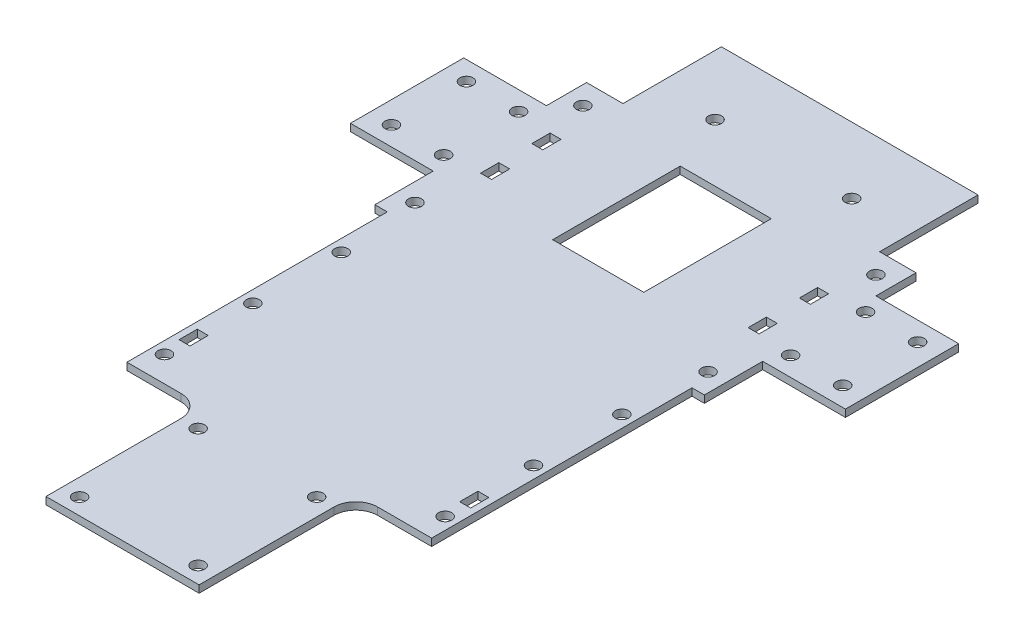
SolidWorks part; units mm, degrees
ref_plane "前视基准面" through (0, 0, 0) normal (0, 0, 1) x (1, 0, 0)
ref_plane "上视基准面" through (0, 0, 0) normal (0, 1, 0) x (1, 0, 0)
ref_plane "右视基准面" through (0, 0, 0) normal (1, 0, 0) x (0, 0, -1)
sketch "Sketch1" plane through (0, 0, 0) normal (0, 1, 0) x (1, 0, 0)
  line L1 (0, 0) -> (50, 0)
  line L2 (0, 0) -> (0, 9.1)
  line L3 (0, 9.1) -> (50, 9.1)
  line L4 (50, 0) -> (50, 9.1)
  dimension "D1" = 50
  dimension "D2" = 9.1
extrude "Boss-Extrude1" add sketch "Sketch1" along normal blind 2
sketch "Sketch2" plane through (0, 2, 0) normal (0, 1, 0) x (1, 0, 0)
  line L0 (50, 9.1) -> (0, 9.1) construction
  line L1 (12.5, 9.1) -> (37.5, 9.1)
  line L2 (12.5, 9.1) -> (12.5, 2.5)
  line L3 (12.5, 2.5) -> (37.5, 2.5)
  line L4 (37.5, 9.1) -> (37.5, 2.5)
  line L5 (0, 9.1) -> (0, 0) construction
  line L6 (50, 0) -> (50, 9.1) construction
  point P8 (50, 4.55)
  dimension "D1" = 6.6
  dimension "D2" = 12.5
  dimension "D3" = 12.5
extrude "Cut-Extrude1" cut sketch "Sketch2" against normal blind 2
sketch "Sketch3" plane through (0, 2, 0) normal (0, 1, 0) x (1, 0, 0)
  line L0 (12.5, 9.1) -> (0, 9.1) construction
  line L1 (50, 9.1) -> (37.5, 9.1) construction
  line L3 (37.5, 2.5) -> (37.5, 9.1) construction
  line L5 (0, 9.1) -> (0, 0) construction
  circle A0 centre (6.25, 5.8) radius 1.8
  circle A1 centre (43.75, 5.8) radius 1.8
  dimension "D1" = 3.6
  dimension "D2" = 3.6
  dimension "D4" = 3.3
  dimension "D3" = 3.3
  dimension "D5" = 6.25
  dimension "D6" = 6.25
extrude "Cut-Extrude2" cut sketch "Sketch3" against normal blind 2
sketch "Sketch4" plane through (0, 2, 0) normal (0, 1, 0) x (1, 0, 0)
  line L0 (0, 0) -> (50, 0) construction
  line L1 (-8.2, 0) -> (58.2, 0)
  line L2 (-8.2, 0) -> (-8.2, -130)
  line L3 (-8.2, -130) -> (58.2, -130)
  line L4 (58.2, 0) -> (58.2, -130)
  line L5 (12.5, 2.5) -> (37.5, 2.5) construction
  point P6 (25, 2.5)
  dimension "D1" = 130
  dimension "D2" = 0
  dimension "D3" = 33.2
  dimension "D4" = 66.4
extrude "Boss-Extrude2" add sketch "Sketch4" against normal blind 2
sketch "Sketch5" plane through (0, 0, 130) normal (0, 0, 1) x (1, 0, 0)
  line L1 (-8.2, 2) -> (58.2, 2)
  line L2 (-8.2, 2) -> (-8.2, 0)
  line L3 (-8.2, 0) -> (58.2, 0)
  line L4 (58.2, 2) -> (58.2, 0)
extrude "Boss-Extrude3" add sketch "Sketch5" along normal blind 2.5
sketch "Sketch6" plane through (0, 2, 0) normal (0, 1, 0) x (1, 0, 0)
  line L1 (-8.2, -132.5) -> (-16.8, -132.5)
  line L2 (-8.2, -132.5) -> (-8.2, -70)
  line L3 (-8.2, -70) -> (-16.8, -70)
  line L4 (-16.8, -132.5) -> (-16.8, -70)
  line L5 (58.2, -132.5) -> (66.8, -132.5)
  line L6 (58.2, -132.5) -> (58.2, -70)
  line L7 (58.2, -70) -> (66.8, -70)
  line L8 (66.8, -132.5) -> (66.8, -70)
  dimension "D1" = 8.6
  dimension "D2" = 8.6
  dimension "D3" = 62.5
  dimension "D4" = 62.5
extrude "Boss-Extrude4" add sketch "Sketch6" against normal blind 2
sketch "Sketch7" plane through (0, 2, 0) normal (0, 1, 0) x (1, 0, 0)
  line L0 (-13.5, -64.2883) -> (-13.5, -157.5169) construction
  line L1 (63.5, -64.2883) -> (63.5, -152.5529) construction
  line L2 (-16.8, -70) -> (-16.8, -132.5) construction
  line L3 (66.8, -132.5) -> (66.8, -70) construction
  line L4 (-8.2, -70) -> (-16.8, -70) construction
  line L5 (66.8, -132.5) -> (-16.8, -132.5) construction
  line L6 (66.8, -70) -> (58.2, -70) construction
  line L7 (-15, -115) -> (-12, -115)
  line L8 (-15, -115) -> (-15, -120)
  line L9 (-15, -120) -> (-12, -120)
  line L10 (-12, -115) -> (-12, -120)
  line L11 (62, -115) -> (65, -115)
  line L12 (62, -115) -> (62, -120)
  line L13 (62, -120) -> (65, -120)
  line L14 (65, -115) -> (65, -120)
  circle A0 centre (-13.5, -77) radius 1.8
  circle A1 centre (-13.5, -101.25) radius 1.8
  circle A2 centre (-13.5, -125.5) radius 1.8
  circle A3 centre (63.5, -77) radius 1.8
  circle A4 centre (63.5, -101.25) radius 1.8
  circle A5 centre (63.5, -125.5) radius 1.8
  dimension "D3" = 3.6
  dimension "D4" = 3.6
  dimension "D6" = 3.6
  dimension "D12" = 3.6
  dimension "D13" = 3.6
  dimension "D14" = 3.6
  dimension "D1" = 3.3
  dimension "D2" = 3.3
  dimension "D5" = 31.25
  dimension "D7" = 7
  dimension "D8" = 1.5
  dimension "D9" = 3
  dimension "D10" = 5
  dimension "D11" = 12.5
  dimension "D15" = 1.5
  dimension "D16" = 3
  dimension "D17" = 7
  dimension "D18" = 7
extrude "Cut-Extrude3" cut sketch "Sketch7" against normal blind 2
sketch "Sketch8" plane through (0, 2, 0) normal (0, 1, 0) x (1, 0, 0)
  line L0 (25, 2.5) -> (25, -143.8166) construction
  line L1 (12.5, 2.5) -> (37.5, 2.5) construction
  line L3 (12.5, 0) -> (37.5, 0)
  line L4 (12.5, 0) -> (12.5, -45)
  line L5 (12.5, -45) -> (37.5, -45)
  line L6 (37.5, 0) -> (37.5, -45)
  dimension "D1" = 25
  dimension "D2" = 12.5
  dimension "D3" = 45
extrude "Cut-Extrude4" cut sketch "Sketch8" against normal blind 20
sketch "Sketch9" plane through (0, 2, 0) normal (0, 1, 0) x (1, 0, 0)
  line L0 (37.5, -45) -> (37.5, 0) construction
  line L1 (12.5, 0) -> (37.5, 0)
  line L2 (12.5, 0) -> (12.5, -10)
  line L3 (12.5, -10) -> (37.5, -10)
  line L4 (37.5, 0) -> (37.5, -10)
  dimension "D1" = 10
extrude "Boss-Extrude5" add sketch "Sketch9" against normal blind 2
sketch "Sketch10" plane through (0, 2, 0) normal (0, 1, 0) x (1, 0, 0)
  line L0 (-8.2, 0) -> (-8.2, -70) construction
  line L1 (-8.2, -16) -> (-42.9, -16)
  line L2 (-8.2, -16) -> (-8.2, -43.07)
  line L3 (-8.2, -43.07) -> (-42.9, -43.07)
  line L4 (-42.9, -16) -> (-42.9, -43.07)
  line L5 (0, 0) -> (-8.2, 0) construction
  line L6 (58.2, -70) -> (58.2, 0) construction
  line L7 (58.2, -16) -> (92.9, -16)
  line L8 (58.2, -16) -> (58.2, -43.07)
  line L9 (58.2, -43.07) -> (92.9, -43.07)
  line L10 (92.9, -16) -> (92.9, -43.07)
  dimension "D1" = 16
  dimension "D2" = 27.07
  dimension "D3" = 34.7
  dimension "D4" = 34.7
extrude "Boss-Extrude6" add sketch "Sketch10" against normal blind 2
sketch "Sketch11" plane through (0, 2, 0) normal (0, 1, 0) x (1, 0, 0)
  line L0 (-48.2559, -39.82) -> (25.7485, -39.82) construction
  line L1 (-47.1851, -19.25) -> (20.7514, -19.25) construction
  line L2 (-8.2, -16) -> (-42.9, -16) construction
  line L3 (-42.9, -43.07) -> (-8.2, -43.07) construction
  line L4 (-42.9, -16) -> (-42.9, -43.07) construction
  circle A0 centre (-36.9, -19.25) radius 1.8
  circle A1 centre (-36.9, -39.82) radius 1.8
  circle A2 centre (-22.6, -19.25) radius 1.8
  circle A3 centre (-22.6, -39.82) radius 1.8
  dimension "D5" = 3.6
  dimension "D6" = 3.6
  dimension "D7" = 3.6
  dimension "D8" = 3.6
  dimension "D10" = 20.3
  dimension "D1" = 3.25
  dimension "D2" = 3.25
  dimension "D3" = 6
  dimension "D4" = 6
  dimension "D9" = 20.3
extrude "Cut-Extrude5" cut sketch "Sketch11" against normal blind 2
sketch "Sketch12" plane through (0, 2, 0) normal (0, 1, 0) x (1, 0, 0)
  line L0 (39.2942, -19.25) -> (115.8735, -19.25) construction
  line L1 (40.8036, -39.82) -> (109.9769, -39.82) construction
  line L2 (92.9, -43.07) -> (92.9, -16) construction
  circle A0 centre (72.6, -19.25) radius 1.8
  circle A1 centre (86.9, -19.25) radius 1.8
  circle A2 centre (72.6, -39.82) radius 1.8
  circle A3 centre (86.9, -39.82) radius 1.8
  dimension "D1" = 3.6
  dimension "D2" = 3.6
  dimension "D5" = 3.6
  dimension "D6" = 3.6
  dimension "D3" = 6
  dimension "D4" = 20.3
extrude "Cut-Extrude6" cut sketch "Sketch12" against normal blind 2
sketch "Sketch13" plane through (-42.9, 0, 0) normal (-1, 0, 0) x (0, 0, 1)
  line L1 (16, 2) -> (14, 2)
  line L2 (16, 2) -> (16, 0)
  line L3 (16, 0) -> (14, 0)
  line L4 (14, 2) -> (14, 0)
  line L5 (43.07, 2) -> (45.07, 2)
  line L6 (43.07, 2) -> (43.07, 0)
  line L7 (43.07, 0) -> (45.07, 0)
  line L8 (45.07, 2) -> (45.07, 0)
  dimension "D1" = 2
  dimension "D2" = 2
extrude "Boss-Extrude7" add sketch "Sketch13" against normal blind 44
sketch "Sketch14" plane through (92.9, 0, 0) normal (1, 0, 0) x (0, 0, -1)
  line L1 (-16, 2) -> (-14, 2)
  line L2 (-16, 2) -> (-16, 0)
  line L3 (-16, 0) -> (-14, 0)
  line L4 (-14, 2) -> (-14, 0)
  line L5 (-43.07, 0) -> (-45.07, 0)
  line L6 (-43.07, 0) -> (-43.07, 2)
  line L7 (-43.07, 2) -> (-45.07, 2)
  line L8 (-45.07, 0) -> (-45.07, 2)
  dimension "D1" = 2
  dimension "D2" = 2
extrude "Boss-Extrude8" add sketch "Sketch14" against normal blind 46
sketch "Sketch16" plane through (0, 2, 0) normal (0, 1, 0) x (1, 0, 0)
  line L0 (66.8, -132.5) -> (-16.8, -132.5) construction
  line L1 (4, -132.5) -> (46, -132.5)
  line L2 (4, -132.5) -> (4, -175.5)
  line L3 (4, -175.5) -> (46, -175.5)
  line L4 (46, -132.5) -> (46, -175.5)
  line L5 (37.5, -45) -> (12.5, -45) construction
  point P6 (25, -45)
  dimension "D1" = 42
  dimension "D2" = 43
  dimension "D3" = 21
extrude "Boss-Extrude10" add sketch "Sketch16" against normal blind 2
sketch "Sketch18" plane through (0, 2, 0) normal (0, 1, 0) x (1, 0, 0)
  line L0 (4, -175.5) -> (46, -175.5) construction
  line L1 (4, -132.5) -> (4, -175.5) construction
  line L2 (46, -175.5) -> (46, -132.5) construction
  line L3 (4, -132.5) -> (-16.8, -132.5) construction
  line L4 (66.8, -132.5) -> (46, -132.5) construction
  circle A0 centre (8.74, -171.03) radius 1.8
  circle A1 centre (41.26, -171.03) radius 1.8
  circle A2 centre (8.74, -138.5) radius 1.8
  circle A3 centre (41.26, -138.5) radius 1.8
  dimension "D3" = 3.6
  dimension "D6" = 3.6
  dimension "D7" = 3.6
  dimension "D8" = 3.6
  dimension "D1" = 4.47
  dimension "D2" = 4.74
  dimension "D4" = 4.47
  dimension "D5" = 4.74
  dimension "D9" = 6
  dimension "D10" = 6
extrude "Cut-Extrude7" cut sketch "Sketch18" against normal blind 2
sketch "Sketch20" plane through (0, 2, 0) normal (0, 1, 0) x (1, 0, 0)
  line L0 (-2, -132.5) -> (4, -132.5)
  line L1 (4, -132.5) -> (-16.8, -132.5) construction
  line L2 (4, -132.5) -> (4, -138.5)
  line L3 (4, -132.5) -> (4, -175.5) construction
  line L4 (46, -138.5) -> (46, -132.5)
  line L5 (46, -175.5) -> (46, -132.5) construction
  line L6 (46, -132.5) -> (52, -132.5)
  line L7 (66.8, -132.5) -> (46, -132.5) construction
  arc A0 (-2, -132.5) -> (4, -138.5) centre (-2, -138.5) cw
  arc A1 (52, -132.5) -> (46, -138.5) centre (52, -138.5) ccw
  dimension "D1" = 6
  dimension "D2" = 6
  dimension "D3" = 6
extrude "Boss-Extrude12" add sketch "Sketch20" against normal blind 2 contours L0 A0 L2 | A1 L6 L4
sketch "Sketch21" plane through (0, 0, -9.1) normal (0, 0, -1) x (-1, 0, 0)
  line L1 (-50, 2) -> (-52, 2)
  line L2 (-50, 2) -> (-50, 0)
  line L3 (-50, 0) -> (-52, 0)
  line L4 (-52, 2) -> (-52, 0)
  line L5 (-37.5, 2) -> (-35.5, 2)
  line L6 (-37.5, 2) -> (-37.5, 0)
  line L7 (-37.5, 0) -> (-35.5, 0)
  line L8 (-35.5, 2) -> (-35.5, 0)
  line L9 (-12.5, 2) -> (-14.5, 2)
  line L10 (-12.5, 2) -> (-12.5, 0)
  line L11 (-12.5, 0) -> (-14.5, 0)
  line L12 (-14.5, 2) -> (-14.5, 0)
  line L13 (0, 2) -> (2, 2)
  line L14 (0, 2) -> (0, 0)
  line L15 (0, 0) -> (2, 0)
  line L16 (2, 2) -> (2, 0)
  dimension "D1" = 2
  dimension "D2" = 2
  dimension "D3" = 2
  dimension "D4" = 2
extrude "Boss-Extrude13" add sketch "Sketch21" against normal blind 10
sketch "Sketch25" plane through (0, 2, 0) normal (0, 1, 0) x (1, 0, 0)
  line L0 (-11.7, -6.4239) -> (-11.7, -56.5762) construction
  line L1 (-8.2, 0) -> (-8.2, -14) construction
  line L2 (61.7, -6.4239) -> (61.7, -56.5762) construction
  line L3 (58.2, -14) -> (58.2, 0) construction
  line L4 (-8.2, -14) -> (-42.9, -14) construction
  line L5 (-13.2, -20) -> (-10.2, -20)
  line L6 (-13.2, -20) -> (-13.2, -25)
  line L7 (-13.2, -25) -> (-10.2, -25)
  line L8 (-10.2, -20) -> (-10.2, -25)
  line L9 (-8.2, -45.07) -> (-42.9, -45.07) construction
  line L10 (-13.2, -34.07) -> (-10.2, -34.07)
  line L11 (-13.2, -34.07) -> (-13.2, -39.07)
  line L12 (-13.2, -39.07) -> (-10.2, -39.07)
  line L13 (-10.2, -34.07) -> (-10.2, -39.07)
  line L14 (58.2, -14) -> (92.9, -14) construction
  line L15 (60.2, -20) -> (63.2, -20)
  line L16 (60.2, -20) -> (60.2, -25)
  line L17 (60.2, -25) -> (63.2, -25)
  line L18 (63.2, -20) -> (63.2, -25)
  line L19 (60.2, -34.07) -> (63.2, -34.07)
  line L20 (60.2, -34.07) -> (60.2, -39.07)
  line L21 (60.2, -39.07) -> (63.2, -39.07)
  line L22 (63.2, -34.07) -> (63.2, -39.07)
  line L23 (58.2, -45.07) -> (92.9, -45.07) construction
  dimension "D1" = 3.5
  dimension "D2" = 3.5
  dimension "D3" = 3
  dimension "D4" = 1.5
  dimension "D5" = 5
  dimension "D6" = 6
  dimension "D7" = 5
  dimension "D8" = 6
  dimension "D9" = 3
  dimension "D10" = 1.5
  dimension "D11" = 1.5
  dimension "D12" = 3
  dimension "D13" = 1.5
  dimension "D14" = 3
  dimension "D15" = 6
  dimension "D16" = 6
extrude "Cut-Extrude8" cut sketch "Sketch25" against normal blind 10
sketch "Sketch26" plane through (0, 2, 0) normal (0, 1, 0) x (1, 0, 0)
  line L1 (-2, 0) -> (-8.2, 0)
  line L2 (-2, 0) -> (-2, 13)
  line L3 (-2, 13) -> (-8.2, 13)
  line L4 (-8.2, 0) -> (-8.2, 13)
  line L5 (58.2, 0) -> (52, 0)
  line L6 (58.2, 0) -> (58.2, 13)
  line L7 (58.2, 13) -> (52, 13)
  line L8 (52, 0) -> (52, 13)
  line L9 (-2, 13) -> (52, 13)
  line L10 (-2, 13) -> (-2, 9.1)
  line L11 (-2, 9.1) -> (52, 9.1)
  line L12 (52, 13) -> (52, 9.1)
  line L13 (35.5, 2.5) -> (14.5, 2.5)
  line L14 (35.5, 2.5) -> (35.5, 9.1)
  line L15 (35.5, 9.1) -> (14.5, 9.1)
  line L16 (14.5, 2.5) -> (14.5, 9.1)
  dimension "D1" = 13
extrude "Boss-Extrude14" add sketch "Sketch26" against normal blind 2 contours L4 L1 L2 L3 | L2 L11 L8 L9 | L16 L13 L14 L11 | L8 L5 L6 L7
sketch "Sketch27" plane through (0, 2, 0) normal (0, 1, 0) x (1, 0, 0)
  line L0 (-8.2, -14) -> (-42.9, -14) construction
  line L1 (-8.2, 13) -> (-10.2, 13)
  line L2 (-8.2, 13) -> (-8.2, -14)
  line L3 (-8.2, -14) -> (-10.2, -14)
  line L4 (-10.2, 13) -> (-10.2, -14)
  line L5 (-8.2, -45.07) -> (-42.9, -45.07) construction
  line L6 (-10.2, -45.07) -> (-8.2, -45.07)
  line L7 (-10.2, -45.07) -> (-10.2, -70)
  line L8 (-10.2, -70) -> (-8.2, -70)
  line L9 (-8.2, -45.07) -> (-8.2, -70)
  line L10 (58.2, -14) -> (92.9, -14) construction
  line L11 (58.2, 13) -> (60.2, 13)
  line L12 (58.2, 13) -> (58.2, -14)
  line L13 (58.2, -14) -> (60.2, -14)
  line L14 (60.2, 13) -> (60.2, -14)
  line L15 (66.8, -70) -> (58.2, -70) construction
  line L16 (58.2, -45.07) -> (60.2, -45.07)
  line L17 (58.2, -45.07) -> (58.2, -70)
  line L18 (58.2, -70) -> (60.2, -70)
  line L19 (60.2, -45.07) -> (60.2, -70)
extrude "Boss-Extrude15" add sketch "Sketch27" against normal blind 2
sketch "Sketch29" plane through (0, 2, 0) normal (0, 1, 0) x (1, 0, 0)
  line L1 (-10.2, -14) -> (-20.2, -14)
  line L2 (-10.2, -14) -> (-10.2, -4)
  line L3 (-10.2, -4) -> (-20.2, -4)
  line L4 (-20.2, -14) -> (-20.2, -4)
  line L5 (-10.2, -45.07) -> (-20.2, -45.07)
  line L6 (-10.2, -45.07) -> (-10.2, -55.07)
  line L7 (-10.2, -55.07) -> (-20.2, -55.07)
  line L8 (-20.2, -45.07) -> (-20.2, -55.07)
  line L9 (60.2, -14) -> (70.2, -14)
  line L10 (60.2, -14) -> (60.2, -4)
  line L11 (60.2, -4) -> (70.2, -4)
  line L12 (70.2, -14) -> (70.2, -4)
  line L13 (60.2, -45.07) -> (70.2, -45.07)
  line L14 (60.2, -45.07) -> (60.2, -55.07)
  line L15 (60.2, -55.07) -> (70.2, -55.07)
  line L16 (70.2, -45.07) -> (70.2, -55.07)
  dimension "D1" = 10
  dimension "D2" = 10
  dimension "D3" = 10
  dimension "D4" = 10
  dimension "D5" = 10
  dimension "D6" = 10
  dimension "D7" = 10
extrude "Boss-Extrude19" add sketch "Sketch29" against normal blind 2
sketch "Sketch41" plane through (0, 2, 0) normal (0, 1, 0) x (1, 0, 0)
  circle A0 centre (-15.2, -9) radius 1.8
  circle A1 centre (-15.2, -50.07) radius 1.8
  circle A2 centre (65.2, -9) radius 1.8
  circle A3 centre (65.2, -50.07) radius 1.8
  dimension "D1" = 3.6
  dimension "D2" = 3.6
  dimension "D3" = 3.6
  dimension "D4" = 3.6
extrude "Cut-Extrude15" cut sketch "Sketch41" against normal blind 2
sketch "Sketch42" plane through (0, 2, 0) normal (0, 1, 0) x (1, 0, 0)
  line L0 (60.2, -70) -> (60.2, -55.07) construction
  line L1 (-10.2, -70) -> (-16.8, -70) construction
  line L2 (-16.8, -70) -> (-10.2, -70)
  line L3 (-10.2, -70) -> (-10.2, -63.4)
  line L4 (60.2, -63.4) -> (60.2, -70)
  line L5 (60.2, -70) -> (66.8, -70)
  arc A0 (-16.8, -70) -> (-10.2, -63.4) centre (-16.8, -63.4) ccw
  arc A1 (66.8, -70) -> (60.2, -63.4) centre (66.8, -63.4) cw
  dimension "D1" = 6.6
extrude "Boss-Extrude26" add sketch "Sketch42" against normal blind 2
sketch "Sketch43" plane through (0, 0, -13) normal (0, 0, -1) x (-1, 0, 0)
  line L1 (10.2, 2) -> (-60.2, 2)
  line L2 (10.2, 2) -> (10.2, 0)
  line L3 (10.2, 0) -> (-60.2, 0)
  line L4 (-60.2, 2) -> (-60.2, 0)
extrude "Boss-Extrude27" add sketch "Sketch43" along normal blind 11
sketch "Sketch44" plane through (0, 2, 0) normal (0, 1, 0) x (1, 0, 0)
  line L0 (-10.2, -55.07) -> (-10.2, -63.4) construction
  line L1 (-20.2, -55.07) -> (-10.2, -55.07)
  line L2 (-20.2, -55.07) -> (-20.2, -60.07)
  line L3 (-20.2, -60.07) -> (-10.2, -60.07)
  line L4 (-10.2, -55.07) -> (-10.2, -60.07)
  line L5 (60.2, -63.4) -> (60.2, -55.07) construction
  line L6 (70.2, -55.07) -> (60.2, -55.07)
  line L7 (70.2, -55.07) -> (70.2, -60.07)
  line L8 (70.2, -60.07) -> (60.2, -60.07)
  line L9 (60.2, -55.07) -> (60.2, -60.07)
  dimension "D1" = 5
extrude "Boss-Extrude28" add sketch "Sketch44" against normal blind 2
sketch "Sketch45" plane through (0, 2, 0) normal (0, 1, 0) x (1, 0, 0)
  circle A0 centre (-15.2, -50.07) radius 1.8
  circle A1 centre (65.2, -50.07) radius 1.8
extrude "Boss-Extrude29" add sketch "Sketch45" against normal blind 2
sketch "Sketch46" plane through (0, 2, 0) normal (0, 1, 0) x (1, 0, 0)
  line L0 (-20.2, -60.07) -> (-10.2, -60.07) construction
  line L1 (60.2, -60.07) -> (70.2, -60.07) construction
  line L2 (-20.2, -45.07) -> (-20.2, -60.07) construction
  line L3 (70.2, -60.07) -> (70.2, -45.07) construction
  circle A0 centre (-15.2, -55.07) radius 1.8
  circle A1 centre (65.2, -55.07) radius 1.8
  dimension "D2" = 3.6
  dimension "D3" = 3.6
  dimension "D1" = 5
  dimension "D4" = 5
  dimension "D5" = 5
  dimension "D6" = 5
extrude "Cut-Extrude16" cut sketch "Sketch46" against normal blind 2
sketch "Sketch47" plane through (0, 2, 0) normal (0, 1, 0) x (1, 0, 0)
  line L0 (-10.2, 24) -> (-10.2, -4) construction
  line L1 (-20.2, -4) -> (-10.2, -4)
  line L2 (-20.2, -4) -> (-20.2, -3)
  line L3 (-20.2, -3) -> (-10.2, -3)
  line L4 (-10.2, -4) -> (-10.2, -3)
  line L5 (-10.2, -60.07) -> (-10.2, -63.4) construction
  line L6 (-20.2, -60.07) -> (-10.2, -60.07)
  line L7 (-20.2, -60.07) -> (-20.2, -61.07)
  line L8 (-20.2, -61.07) -> (-10.2, -61.07)
  line L9 (-10.2, -60.07) -> (-10.2, -61.07)
  line L10 (60.2, -63.4) -> (60.2, -60.07) construction
  line L11 (60.2, -4) -> (70.2, -4)
  line L12 (60.2, -4) -> (60.2, -3)
  line L13 (60.2, -3) -> (70.2, -3)
  line L14 (70.2, -4) -> (70.2, -3)
  line L15 (70.2, -60.07) -> (60.2, -60.07)
  line L16 (70.2, -60.07) -> (70.2, -61.07)
  line L17 (70.2, -61.07) -> (60.2, -61.07)
  line L18 (60.2, -60.07) -> (60.2, -61.07)
  dimension "D1" = 1
  dimension "D2" = 1
extrude "Boss-Extrude30" add sketch "Sketch47" against normal blind 2
sketch "Sketch48" plane through (0, 2, 0) normal (0, 1, 0) x (1, 0, 0)
  line L0 (66.8, -132.5) -> (66.8, -70) construction
  line L1 (-16.8, -70) -> (-10.2, -70)
  line L2 (-16.8, -70) -> (-16.8, -61.07)
  line L3 (-16.8, -61.07) -> (-10.2, -61.07)
  line L4 (-10.2, -70) -> (-10.2, -61.07)
  line L5 (66.8, -70) -> (60.2, -70)
  line L6 (66.8, -70) -> (66.8, -61.07)
  line L7 (66.8, -61.07) -> (60.2, -61.07)
  line L8 (60.2, -70) -> (60.2, -61.07)
  arc A0 (60.2, -63.4) -> (66.8, -70) centre (66.8, -63.4) ccw construction
extrude "Boss-Extrude31" add sketch "Sketch48" against normal blind 2
